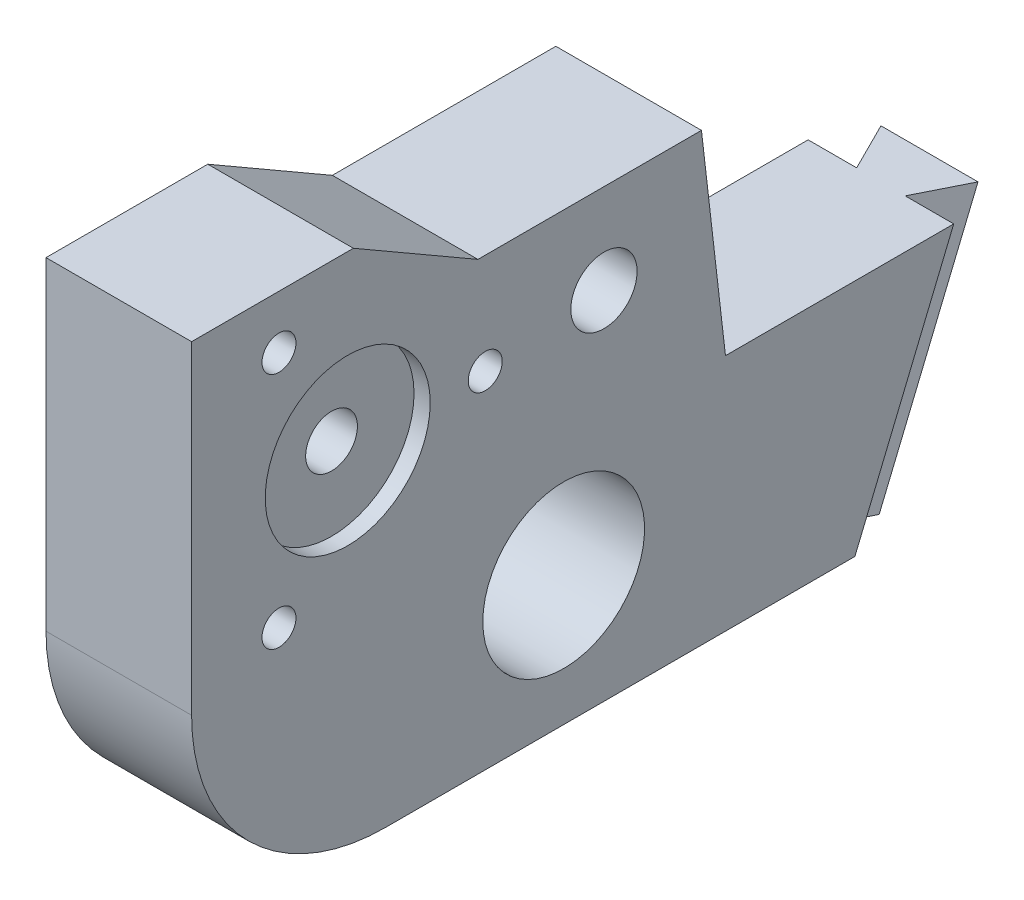
SolidWorks part; units mm, degrees
ref_plane "Front Plane" through (0, 0, 0) normal (0, 0, 1) x (1, 0, 0)
ref_plane "Top Plane" through (0, 0, 0) normal (0, 1, 0) x (1, 0, 0)
ref_plane "Right Plane" through (0, 0, 0) normal (1, 0, 0) x (0, 0, -1)
ref_plane "Plane1" through (-2, 0, 0) normal (-1, 0, 0) x (0, -1, 0)
sketch "Sketch1" plane through (-2, 0, 0) normal (-1, 0, 0) x (0, -1, 0)
  line L0 (-24, 51) -> (-24, -1)
  line L1 (-24, -1) -> (8, -1)
  line L2 (8, -1) -> (8, 51)
  line L3 (8, 51) -> (-24, 51)
extrude "Boss-Extrude1" add sketch "Sketch1" against normal blind 9
sketch "Sketch2" plane through (7, 0, 0) normal (1, 0, 0) x (0, 0, -1)
  line L0 (-47, 15.25) -> (4, 15.25)
  line L1 (4, 15.25) -> (4, 24)
  line L2 (4, 24) -> (-47, 24)
  line L3 (-47, 24) -> (-47, 15.25)
extrude "Cut-Extrude1" [suppressed] cut sketch "Sketch2" against normal through all
sketch "Sketch3" plane through (7, 0, 0) normal (1, 0, 0) x (0, 0, -1)
  line L0 (4, 6.75) -> (-18, 6.75)
  line L1 (4, 6.75) -> (4, 24)
  line L2 (4, 24) -> (-20, 24)
  line L3 (-51, 24) -> (1, 24) construction
  line L4 (-18, 6.75) -> (-20, 24)
  dimension "D2" = 22
  dimension "D3" = 24
  dimension "D4" = 6.75
  dimension "D5" = 4
extrude "Cut-Extrude2" cut sketch "Sketch3" against normal through all
hole_wizard "Ø10.0 (10) Diameter Hole1" positions "Sketch6" profile "Sketch5" hole size "Ø10.0" standard "ANSI Metric"
sketch "Sketch6" plane through (-2, 0, 0) normal (-1, 0, 0) x (0, 0, 1)
  point P0 (28, 0)
sketch "Sketch5" plane through (-2, 0, 28) normal (0, 1, 0) x (0, 0, 1)
  line L0 (0, 0) -> (0, 9)
  line L1 (0, 9) -> (5, 9)
  line L2 (5, 9) -> (5, 0)
  line L5 (5, 0) -> (0, 0)
  line L11 (0, -6.35) -> (0, 107.95) construction
  dimension "Thru Hole Dia." = 10
  dimension "Thru Hole Depth" = 9
hole_wizard "M4x0.7 Tapped Hole1" [suppressed] positions "Sketch8" profile "Sketch7" tap size "M4x0.7" standard "ANSI Metric"
sketch "Sketch8" plane through (-2, 0, 0) normal (-1, 0, 0) x (0, 0, 1)
  point P0 (38.9682, 5)
  point P1 (51.7182, -2.3612)
  point P2 (51.7182, 12.3612)
sketch "Sketch7" plane through (-2, 5, 38.9682) normal (0, 1, 0) x (0, 0, 1)
  line L0 (0, 0) -> (0, 7)
  line L1 (0, 7) -> (1.05, 7)
  line L3 (1.05, 7) -> (1.05, 2)
  line L4 (1.05, 2) -> (2, 2)
  line L5 (2, 2) -> (2, 0)
  line L7 (2, 0) -> (0, 0)
  line L11 (0, -6.35) -> (0, 107.95) construction
  dimension "Thru Tap Drill Dia." = 2.1
  dimension "Thru Tap Drill Depth" = 7
  dimension "Thread Major Dia." = 4
  dimension "Thread Depth" = 2
hole_wizard "CBORE for M3 Hex Head Machine Screw1" [suppressed] positions "Sketch10" profile "Sketch9" counterbore size "M3" standard "ANSI Metric"
sketch "Sketch10" plane through (5, 0, 0) normal (1, 0, 0) x (0, 0, -1)
  point P0 (-47.4682, 5)
sketch "Sketch9" plane through (5, 5, 47.4682) normal (0, 1, 0) x (0, 0, -1)
  line L0 (0, 0) -> (0, 7)
  line L1 (0, 7) -> (1.6, 7)
  line L3 (1.6, 7) -> (1.6, 1)
  line L4 (1.6, 1) -> (5.1, 1)
  line L5 (5.1, 1) -> (5.1, 0)
  line L7 (5.1, 0) -> (0, 0)
  line L11 (0, -6.35) -> (0, 107.95) construction
  dimension "Thru Hole Dia." = 3.2
  dimension "Thru Hole Depth" = 7
  dimension "C'Bore Dia." = 10.2
  dimension "C'Bore Depth" = 1
hole_wizard "Ø4.1 (4.1) Diameter Hole1" [suppressed] positions "Sketch14" profile "Sketch13" hole size "Ø4.1" standard "ANSI Metric"
sketch "Sketch14" plane through (-2, 0, 0) normal (-1, 0, 0) x (0, 0, 1)
  point P0 (32, 12)
sketch "Sketch13" plane through (-2, 12, 32) normal (0, 1, 0) x (0, 0, 1)
  line L0 (0, 0) -> (0, 7)
  line L1 (0, 7) -> (2.05, 7)
  line L2 (2.05, 7) -> (2.05, 0)
  line L5 (2.05, 0) -> (0, 0)
  line L11 (0, -6.35) -> (0, 107.95) construction
  dimension "Thru Hole Dia." = 4.1
  dimension "Thru Hole Depth" = 7
hole_wizard "Ø4.1 (4.1) Diameter Hole2" [suppressed] positions "Sketch20" profile "Sketch19" hole size "Ø4.1" standard "ANSI Metric"
sketch "Sketch20" plane through (5, 0, 0) normal (1, 0, 0) x (0, 0, -1)
  point P0 (-55, 20.5)
sketch "Sketch19" plane through (5, 20.5, 55) normal (0, 1, 0) x (0, 0, -1)
  line L0 (0, 0) -> (0, 7)
  line L1 (0, 7) -> (2.05, 7)
  line L2 (2.05, 7) -> (2.05, 0)
  line L5 (2.05, 0) -> (0, 0)
  line L11 (0, -6.35) -> (0, 107.95) construction
  dimension "Thru Hole Dia." = 4.1
  dimension "Thru Hole Depth" = 7
fillet "Fillet3" radius 12 1 edges at (2.5, -8, 51)
sketch "Sketch21" plane through (0, -8, 0) normal (0, -1, 0) x (1, 0, 0)
  line L0 (7, -1) -> (-2, -1) construction
  line L1 (7, 7) -> (5.5, 7)
  line L2 (-2, 50) -> (-2, -50) construction
  line L3 (4, 10) -> (7, 10)
  line L4 (1, 10) -> (-0.5, 7)
  line L5 (4, 10) -> (5.5, 7)
  line L7 (1, 10) -> (-2, 10)
  line L8 (2.5, 8) -> (2.5, 14) construction
  line L9 (-2, 10) -> (-2, 7)
  line L10 (-2, 7) -> (-0.5, 7)
  line L11 (7, 10) -> (7, 7)
  dimension "D1" = 1.5
  dimension "D2" = 3
  dimension "D3" = 8
  dimension "D4" = 3
  dimension "D5" = 4.5
sketch "Sketch22" plane through (-2, 0, 0) normal (-1, 0, 0) x (0, -1, 0)
  line L0 (8, 11) -> (-6.75, 4.8903)
  line L1 (8, 8) -> (8, 14) construction
  line L2 (-6.75, 18) -> (-6.75, -1) construction
  line L3 (-6.75, -1) -> (8, -1) construction
  dimension "D1" = 22.5
sweep "Cut-Sweep1" cut profiles "Sketch21" path "Sketch22"
sketch "Sketch23" plane through (-2, 0, 0) normal (-1, 0, 0) x (0, 0, 1)
  line L0 (-1, 6.75) -> (-1, -8)
  line L1 (-1, -8) -> (7, -8)
  line L2 (7, -8) -> (0.8903, 6.75)
  line L3 (0.8903, 6.75) -> (-1, 6.75)
extrude "Cut-Extrude3" cut sketch "Sketch23" against normal through all both and the other way through all
sketch "Sketch25" plane through (-2, 0, 0) normal (-1, 0, 0) x (0, 0, 1)
  line L0 (51, 4) -> (51, 24) construction
  line L1 (45.5998, 5.9885) -> (45.5998, 20.711)
  line L2 (45.5998, 20.711) -> (32.8498, 13.3498)
  line L3 (32.8498, 13.3498) -> (45.5998, 5.9885)
  line L4 (41.3498, 13.3498) -> (28, 0) construction
  line L5 (10, -8) -> (39, -8) construction
  line L6 (51, 24) -> (20, 24) construction
  circle A0 centre (41.3498, 13.3498) radius 4.25 construction
  circle A3 centre (28, 0) radius 5 construction
  point P11 (25.5108, 14)
  dimension "D2" = 18.8794
  dimension "D1" = 8.5
  dimension "D3" = 45
  dimension "D4" = 10
hole_wizard "M4x0.7 Tapped Hole2" positions "3DSketch4" profile "Sketch28" tap size "M4x0.7" standard "ANSI Metric" end condition through all
sketch3d "3DSketch4"
  point P0 (-2, 13.3498, 32.8498)
  point P3 (-2, 20.711, 45.5998)
  point P6 (-2, 5.9885, 45.5998)
sketch "Sketch28" plane through (-2, 13.3498, 32.8498) normal (0, 1, 0) x (0, 0, 1)
  line L0 (0, 0) -> (0, 9)
  line L1 (0, 9) -> (1.05, 9)
  line L3 (1.05, 9) -> (1.05, 2)
  line L4 (1.05, 2) -> (1.65, 2)
  line L5 (1.65, 2) -> (1.65, 0)
  line L7 (1.65, 0) -> (0, 0)
  line L11 (0, -6.35) -> (0, 107.95) construction
  dimension "Thru Tap Drill Dia." = 2.1
  dimension "Thru Tap Drill Depth" = 9
  dimension "Thread Major Dia." = 3.3
  dimension "Thread Depth" = 2
sketch "Sketch33" plane through (7, 0, 0) normal (1, 0, 0) x (0, 0, -1)
  line L1 (-32.8498, 13.3498) -> (-45.5998, 20.711)
  line L2 (-45.5998, 20.711) -> (-45.5998, 5.9885)
  line L3 (-45.5998, 5.9885) -> (-32.8498, 13.3498)
  circle A0 centre (-41.3498, 13.3498) radius 4.25 construction
hole_wizard "CBORE for M3 Hex Head Machine Screw5" positions "3DSketch10" profile "Sketch35" counterbore size "M3" standard "ANSI Metric" end condition through all
sketch3d "3DSketch10"
  point P0 (7, 13.3498, 41.3498)
sketch "Sketch35" plane through (7, 13.3498, 41.3498) normal (0, 1, 0) x (0, 0, -1)
  line L0 (0, 0) -> (0, 9)
  line L1 (0, 9) -> (1.6, 9)
  line L3 (1.6, 9) -> (1.6, 1)
  line L4 (1.6, 1) -> (5.1, 1)
  line L5 (5.1, 1) -> (5.1, 0)
  line L7 (5.1, 0) -> (0, 0)
  line L11 (0, -6.35) -> (0, 107.95) construction
  dimension "Thru Hole Dia." = 3.2
  dimension "Thru Hole Depth" = 9
  dimension "C'Bore Dia." = 10.2
  dimension "C'Bore Depth" = 1
hole_wizard "Ø4.1 (4.1) Diameter Hole3" positions "3DSketch11" profile "Sketch36" hole size "Ø4.1" standard "ANSI Metric" end condition through all
sketch3d "3DSketch11"
  point P0 (-2, 14, 25.5108)
sketch "Sketch36" plane through (-2, 14, 25.5108) normal (0, 1, 0) x (0, 0, 1)
  line L0 (0, 0) -> (0, 9)
  line L1 (0, 9) -> (2.05, 9)
  line L2 (2.05, 9) -> (2.05, 0)
  line L5 (2.05, 0) -> (0, 0)
  line L11 (0, -6.35) -> (0, 107.95) construction
  dimension "Thru Hole Dia." = 4.1
  dimension "Thru Hole Depth" = 9
sketch "Sketch37" plane through (-2, 0, 0) normal (-1, 0, 0) x (0, 0, 1)
  line L0 (41, 24) -> (20, 24)
  line L2 (51, 24) -> (20, 24) construction
  line L4 (20, 24) -> (19.8741, 22.9141)
  line L5 (20, 24) -> (18, 6.75) construction
  line L11 (19.4846, 19.5547) -> (33.3004, 19.5547)
  line L12 (33.3004, 19.5547) -> (41, 24)
  line L13 (45.5998, 20.711) -> (32.8498, 13.3498) construction
  line L14 (51, 4) -> (51, 24) construction
  dimension "D1" = 10
extrude "Cut-Extrude4" cut sketch "Sketch37" against normal through all both and the other way through all
